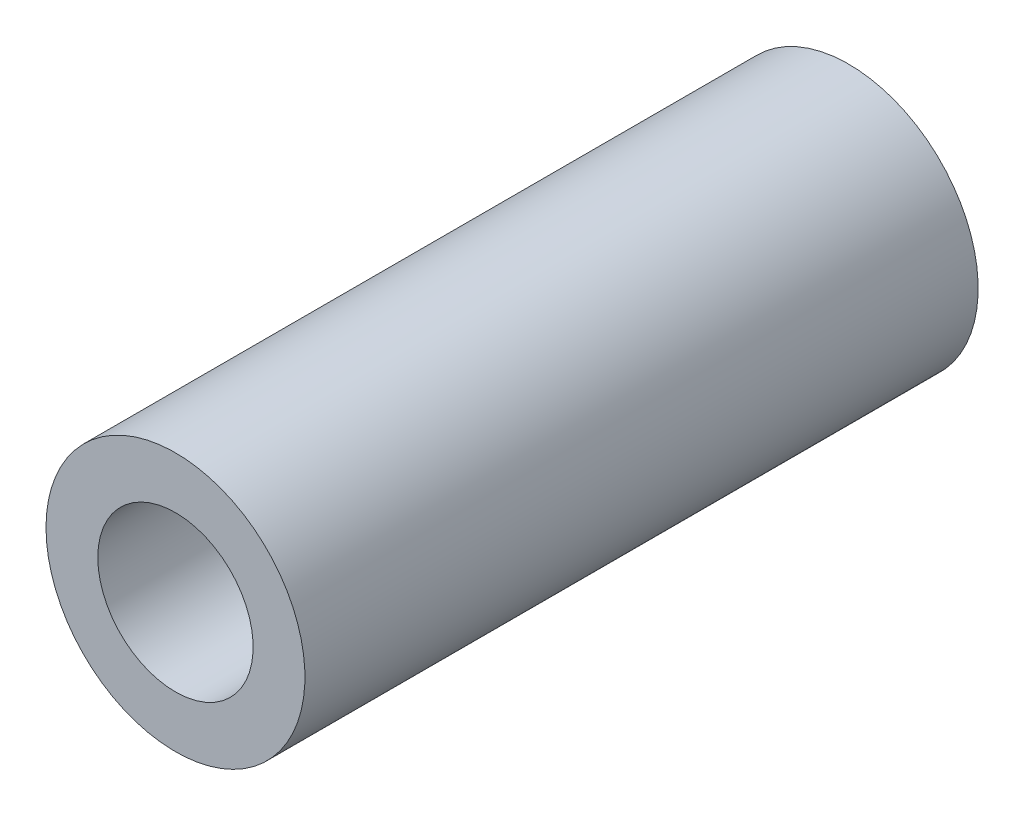
SolidWorks part; units mm, degrees
material "ABS"
ref_plane "前视基准面" through (0, 0, 0) normal (0, 0, 1) x (1, 0, 0)
ref_plane "上视基准面" through (0, 0, 0) normal (0, 1, 0) x (1, 0, 0)
ref_plane "右视基准面" through (0, 0, 0) normal (1, 0, 0) x (0, 0, -1)
sketch "草图1" plane through (0, 0, 0) normal (0, 0, 1) x (1, 0, 0)
  circle A0 centre (0, 0) radius 1.5
  circle A1 centre (0, 0) radius 2.5
  dimension "D1" = 3
  dimension "D2" = 5
extrude "凸台-拉伸1" add sketch "草图1" along normal mid plane 13
